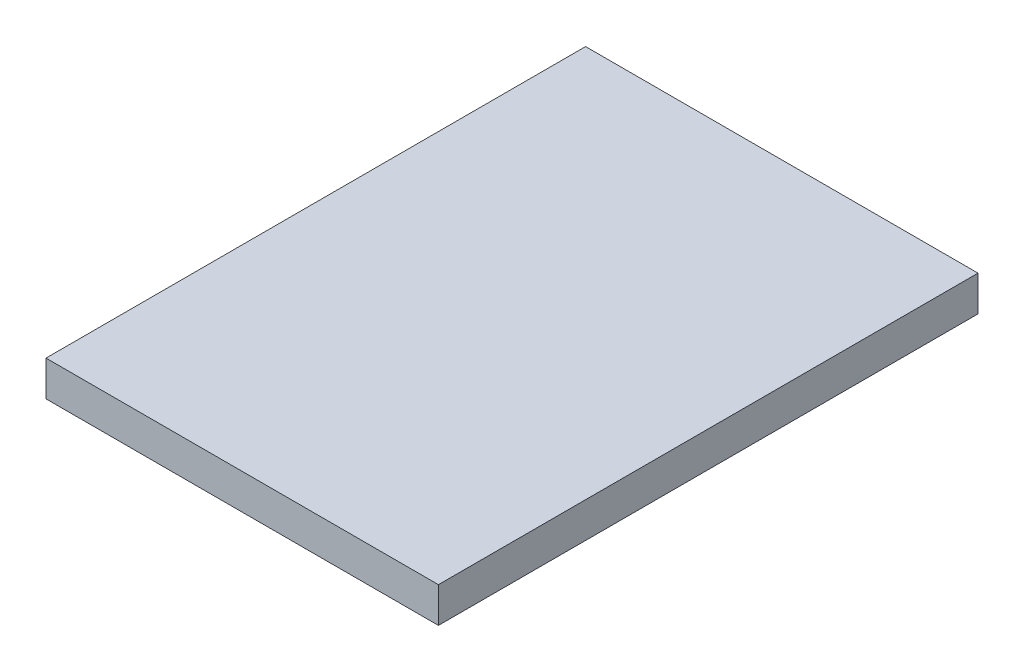
SolidWorks part; units mm, degrees
ref_plane "Front" through (0, 0, 0) normal (0, 0, 1) x (1, 0, 0)
ref_plane "Top" through (0, 0, 0) normal (0, 1, 0) x (1, 0, 0)
ref_plane "Right" through (0, 0, 0) normal (1, 0, 0) x (0, 0, -1)
sketch "Sketch1" plane through (0, 0, 0) normal (0, 1, 0) x (1, 0, 0)
  line L1 (101.6, -139.7) -> (-101.6, -139.7)
  line L2 (101.6, -139.7) -> (101.6, 139.7)
  line L3 (101.6, 139.7) -> (-101.6, 139.7)
  line L4 (-101.6, -139.7) -> (-101.6, 139.7)
  line L5 (101.6, -139.7) -> (-101.6, 139.7) construction
  line L6 (101.6, 139.7) -> (-101.6, -139.7) construction
  point P0 (0, 0)
  dimension "D1" = 203.2
  dimension "D2" = 279.4
extrude "Boss-Extrude1" add sketch "Sketch1" along normal blind 18.288
